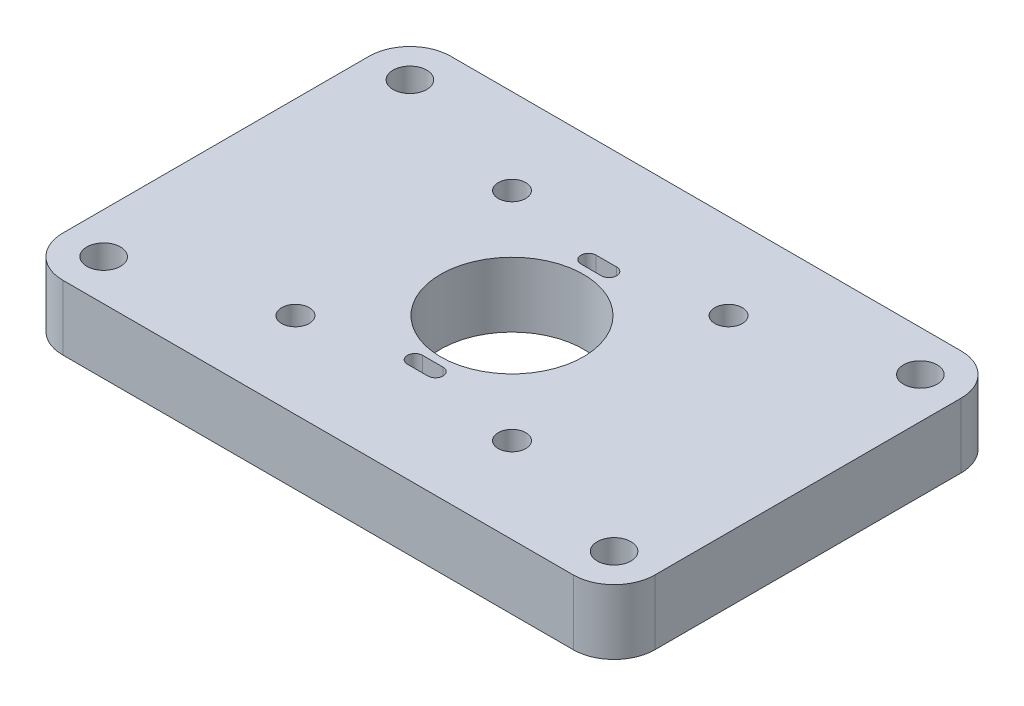
SolidWorks part; units mm, degrees
material "Acrylic (Medium-high impact)"
ref_plane "Front Plane" through (0, 0, 0) normal (0, 0, 1) x (1, 0, 0)
ref_plane "Top Plane" through (0, 0, 0) normal (0, 1, 0) x (1, 0, 0)
ref_plane "Right Plane" through (0, 0, 0) normal (1, 0, 0) x (0, 0, -1)
sketch "Sketch1" plane through (0, 0, 0) normal (0, 1, 0) x (1, 0, 0)
  line L0 (0, 15) -> (50, 15) construction
  line L1 (0, 0) -> (50, 0) construction
  line L2 (0, 0) -> (0, 30) construction
  line L3 (0, 30) -> (50, 30) construction
  line L4 (50, 0) -> (50, 30) construction
  line L5 (25, 15) -> (25, 34) construction
  line L6 (-4, 34) -> (54, 34)
  line L7 (-4, 34) -> (-4, -4)
  line L8 (-4, -4) -> (54, -4)
  line L9 (54, 34) -> (54, -4)
  line L10 (25, 15) -> (25, -4) construction
  circle A0 centre (25, 15) radius 7
  circle A1 centre (0, 30) radius 1.65
  circle A2 centre (50, 30) radius 1.65
  circle A3 centre (50, 0) radius 1.65
  circle A4 centre (0, 0) radius 1.65
  dimension "D1" = 14
  dimension "D2" = 3.3
  dimension "D3" = 50
  dimension "D4" = 30
  dimension "D5" = 4
  dimension "D6" = 4
extrude "Boss-Extrude1" add sketch "Sketch1" along normal blind 6.35
fillet "Fillet1" radius 4 4 edges at (-4, 3.175, -34) (54, 3.175, -34) (54, 3.175, 4) (-4, 3.175, 4)
sketch "Sketch2" plane through (0, 6.35, 0) normal (0, 1, 0) x (1, 0, 0)
  line L0 (25, 15) -> (25, 23.5) construction
  line L1 (24, 23.5) -> (26, 23.5) construction
  line L2 (24, 24.25) -> (26, 24.25)
  line L3 (24, 22.75) -> (26, 22.75)
  line L4 (25, 15) -> (54, 15) construction
  line L5 (54, 0) -> (54, 30) construction
  line L6 (24, 6.5) -> (26, 6.5) construction
  line L7 (24, 5.75) -> (26, 5.75)
  line L8 (24, 7.25) -> (26, 7.25)
  arc A0 (24, 24.25) -> (24, 22.75) centre (24, 23.5) ccw
  arc A1 (26, 22.75) -> (26, 24.25) centre (26, 23.5) ccw
  arc A2 (24, 5.75) -> (24, 7.25) centre (24, 6.5) cw
  arc A3 (26, 7.25) -> (26, 5.75) centre (26, 6.5) cw
  point P5 (25, 23.5)
  point P15 (25, 6.5)
  dimension "D1" = 1.5
  dimension "D2" = 2
  dimension "D3" = 8.5
extrude "Cut-Extrude1" cut sketch "Sketch2" against normal through all
sketch "Sketch3" plane through (0, 6.35, 0) normal (0, 1, 0) x (1, 0, 0)
  line L0 (14.3934, 25.6066) -> (25, 15) construction
  line L1 (25, 15) -> (10, 15) construction
  circle A0 centre (25, 15) radius 15 construction
  circle A1 centre (35.6066, 25.6066) radius 1.35
  circle A2 centre (35.6066, 4.3934) radius 1.35
  circle A3 centre (14.3934, 25.6066) radius 1.35
  circle A4 centre (14.3934, 4.3934) radius 1.35
  point P15 (25, 15)
  dimension "D1" = 2.7
  dimension "D2" = 30
  dimension "D3" = 45
  dimension "D4" = 4
extrude "Cut-Extrude2" cut sketch "Sketch3" against normal through all
